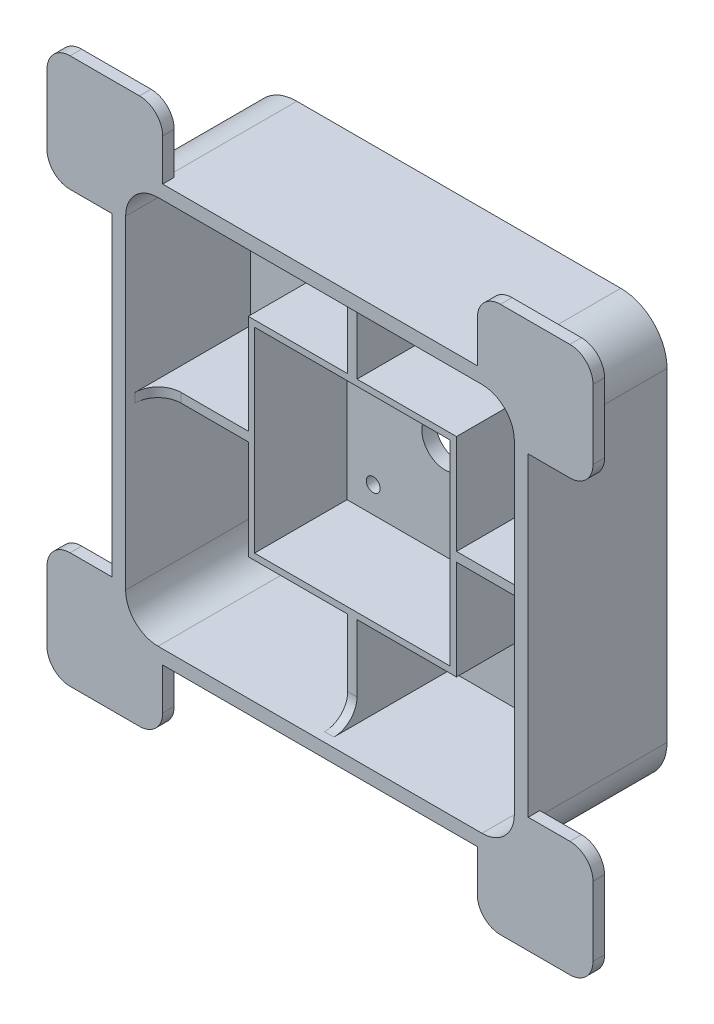
SolidWorks part; units mm, degrees
material "尼龙 101"
ref_plane "前视基准面" through (0, 0, 0) normal (0, 0, 1) x (1, 0, 0)
ref_plane "上视基准面" through (0, 0, 0) normal (0, 1, 0) x (1, 0, 0)
ref_plane "右视基准面" through (0, 0, 0) normal (1, 0, 0) x (0, 0, -1)
sketch "草图1" plane through (0, 0, 0) normal (0, 0, 1) x (1, 0, 0)
  line L1 (-35, 45) -> (35, 45)
  line L2 (-45, 35) -> (-45, -35)
  line L3 (-35, -45) -> (35, -45)
  line L4 (45, 35) -> (45, -35)
  line L5 (-45, 45) -> (45, -45) construction
  line L6 (-45, -45) -> (45, 45) construction
  arc A0 (-45, -35) -> (-35, -45) centre (-35, -35) ccw
  arc A1 (35, -45) -> (45, -35) centre (35, -35) ccw
  arc A2 (35, 45) -> (45, 35) centre (35, 35) cw
  arc A3 (-35, 45) -> (-45, 35) centre (-35, 35) ccw
  point P0 (0, 0)
  dimension "D3" = 10
  dimension "D1" = 90
  dimension "D2" = 90
extrude "凸台-拉伸1" add sketch "草图1" along normal blind 30
shell "抽壳1" thickness 3
sketch "草图3" plane through (0, 0, 30) normal (0, 0, 1) x (1, 0, 0)
  line L1 (0, 0) -> (0, 55.6478) construction
  line L2 (0, 0) -> (103.6974, 0) construction
  circle A0 centre (-34, 34) radius 3
  circle A1 centre (34, 34) radius 3
  circle A2 centre (34, -34) radius 3
  circle A3 centre (-34, -34) radius 3
  dimension "D3" = 6
  dimension "D4" = 6
  dimension "D5" = 6
  dimension "D6" = 6
  dimension "D1" = 68
  dimension "D2" = 68
extrude "切除-拉伸1" cut sketch "草图3" against normal up to next
sketch "草图4" plane through (0, 0, 3) normal (0, 0, 1) x (1, 0, 0)
  line L1 (-21.15, -21.15) -> (21.15, -21.15)
  line L2 (-21.15, -21.15) -> (-21.15, 21.15)
  line L3 (-21.15, 21.15) -> (21.15, 21.15)
  line L4 (21.15, -21.15) -> (21.15, 21.15)
  line L5 (-21.15, -21.15) -> (21.15, 21.15) construction
  line L6 (-21.15, 21.15) -> (21.15, -21.15) construction
  line L7 (-22.5, -22.5) -> (22.5, -22.5)
  line L8 (-22.5, -22.5) -> (-22.5, 22.5)
  line L9 (-22.5, 22.5) -> (22.5, 22.5)
  line L10 (22.5, -22.5) -> (22.5, 22.5)
  line L11 (-22.5, -22.5) -> (22.5, 22.5) construction
  line L12 (-22.5, 22.5) -> (22.5, -22.5) construction
  point P0 (0, 0)
  point P6 (0, 0)
  dimension "D1" = 42.3
  dimension "D2" = 42.3
  dimension "D3" = 45
  dimension "D4" = 45
extrude "凸台-拉伸3" add sketch "草图4" along normal blind 20
sketch "草图11" plane through (0, 0, 3) normal (0, 0, 1) x (1, 0, 0)
  line L0 (-15.5, -15.5) -> (-15.5, 15.5) construction
  line L1 (-15.5, 15.5) -> (15.5, 15.5) construction
  line L2 (15.5, 15.5) -> (15.5, -15.5) construction
  line L3 (15.5, -15.5) -> (-15.5, -15.5) construction
  line L4 (0, 0) -> (34.4126, 0) construction
  line L5 (0, 0) -> (0, 49.7231) construction
  circle A0 centre (-15.5, -15.5) radius 1.5
  circle A1 centre (15.5, -15.5) radius 1.5
  circle A2 centre (15.5, 15.5) radius 1.5
  circle A3 centre (-15.5, 15.5) radius 1.5
  point P12 (0, 0)
  dimension "D3" = 3
  dimension "D4" = 3
  dimension "D5" = 3
  dimension "D6" = 3
  dimension "D1" = 31
  dimension "D2" = 31
extrude "切除-拉伸4" cut sketch "草图11" against normal through all
sketch "草图7" plane through (0, 0, 3) normal (0, 0, 1) x (1, 0, 0)
  line L0 (22.5, 22.5) -> (-22.5, 22.5) construction
  line L1 (-1, 42) -> (1, 42)
  line L2 (-1, 42) -> (-1, 22.5)
  line L3 (-1, 22.5) -> (1, 22.5)
  line L4 (1, 42) -> (1, 22.5)
  line L5 (-1, 42) -> (1, 22.5) construction
  line L6 (-1, 22.5) -> (1, 42) construction
  line L7 (-35, -42) -> (35, -42) construction
  line L8 (-1, -22.5) -> (1, -22.5)
  line L9 (-1, -22.5) -> (-1, -42)
  line L10 (-1, -42) -> (1, -42)
  line L11 (1, -22.5) -> (1, -42)
  line L12 (-1, -22.5) -> (1, -42) construction
  line L13 (-1, -42) -> (1, -22.5) construction
  line L14 (0, 32.25) -> (0, 0) construction
  line L15 (0, 0) -> (0, -32.25) construction
  line L16 (35, 42) -> (-35, 42) construction
  line L17 (-22.5, -22.5) -> (22.5, -22.5) construction
  point P0 (0, 32.25)
  point P7 (0, -32.25)
  dimension "D1" = 2
  dimension "D2" = 2
extrude "凸台-拉伸5" add sketch "草图7" along normal up to surface (20 mm away) up to face at (0, 0, 23)
ref_axis "基准轴1" through (0, 0, -2) along (0, 0, 1)
pattern_circular "阵列(圆周)1" count 2 over 90 about axis through (0, 0, -2) along (0, 0, 1) of "凸台-拉伸5"
sketch "草图10" plane through (0, 0, 0) normal (0, 0, -1) x (-1, 0, 0)
  circle A0 centre (0, 0) radius 5
  dimension "D1" = 10
extrude "切除-拉伸3" cut sketch "草图10" against normal through all
fillet "圆角1" radius 5 4 edges at (-42, 0, 23) (42, 0, 23) (0, -42, 23) (0, 42, 23)
sketch "草图12" plane through (0, 0, 30) normal (0, 0, 1) x (1, 0, 0)
  line L0 (34, 42) -> (35, 42)
  line L1 (42, 34) -> (54, 34)
  line L2 (34, 42) -> (34, 54)
  line L3 (39, 59) -> (54, 59)
  line L4 (59, 39) -> (59, 54)
  line L5 (42, -34) -> (54, -34)
  line L6 (34, -42) -> (34, -54)
  line L7 (39, -59) -> (54, -59)
  line L8 (59, -39) -> (59, -54)
  line L17 (35, 42) -> (-35, 42) construction
  line L18 (42, 35) -> (42, 34)
  line L19 (42, -35) -> (42, 35) construction
  line L20 (35, -42) -> (34, -42)
  line L21 (-35, -42) -> (35, -42) construction
  line L22 (42, -35) -> (42, -34)
  line L23 (0, 0) -> (0, -109.4281) construction
  line L24 (-42, -35) -> (-42, -34)
  line L25 (-35, -42) -> (-34, -42)
  line L26 (-42, 35) -> (-42, 34)
  line L27 (-59, -39) -> (-59, -54)
  line L28 (-39, -59) -> (-54, -59)
  line L29 (-34, -42) -> (-34, -54)
  line L30 (-42, -34) -> (-54, -34)
  line L31 (-59, 39) -> (-59, 54)
  line L32 (-39, 59) -> (-54, 59)
  line L33 (-34, 42) -> (-34, 54)
  line L34 (-42, 34) -> (-54, 34)
  line L35 (-34, 42) -> (-35, 42)
  arc A0 (35, 42) -> (42, 35) centre (35, 35) cw
  arc A4 (42, -35) -> (35, -42) centre (35, -35) cw
  arc A5 (34, -54) -> (39, -59) centre (39, -54) ccw
  arc A6 (54, -59) -> (59, -54) centre (54, -54) ccw
  arc A7 (54, -34) -> (59, -39) centre (54, -39) cw
  arc A8 (34, 54) -> (39, 59) centre (39, 54) cw
  arc A9 (54, 34) -> (59, 39) centre (54, 39) ccw
  arc A10 (54, 59) -> (59, 54) centre (54, 54) cw
  arc A19 (-54, 59) -> (-59, 54) centre (-54, 54) ccw
  arc A20 (-54, 34) -> (-59, 39) centre (-54, 39) cw
  arc A21 (-34, 54) -> (-39, 59) centre (-39, 54) ccw
  arc A22 (-54, -34) -> (-59, -39) centre (-54, -39) ccw
  arc A23 (-54, -59) -> (-59, -54) centre (-54, -54) cw
  arc A24 (-34, -54) -> (-39, -59) centre (-39, -54) cw
  arc A25 (-42, -35) -> (-35, -42) centre (-35, -35) ccw
  arc A26 (-35, 42) -> (-42, 35) centre (-35, 35) ccw
  point P49 (59, 34)
  point P52 (59, 59)
  point P76 (-59, 59)
  point P77 (-59, 34)
  dimension "D5" = 5
  dimension "D1" = 25
  dimension "D2" = 25
  dimension "D3" = 25
  dimension "D4" = 25
extrude "凸台-拉伸6" add sketch "草图12" against normal blind 2.5
